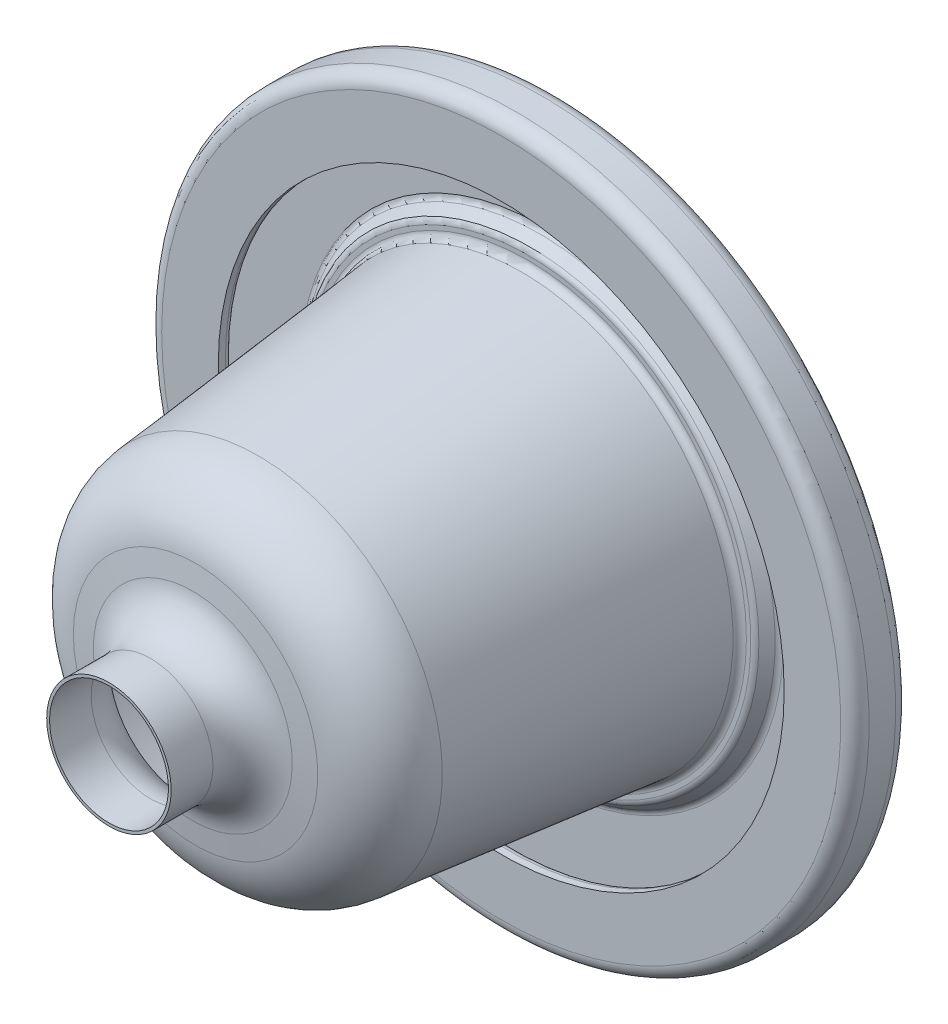
SolidWorks part; units mm, degrees
ref_plane "Front Plane" through (0, 0, 0) normal (0, 0, 1) x (1, 0, 0)
ref_plane "Top Plane" through (0, 0, 0) normal (0, 1, 0) x (1, 0, 0)
ref_plane "Right Plane" through (0, 0, 0) normal (1, 0, 0) x (0, 0, -1)
sketch "Sketch1" plane through (0, 0, 0) normal (0, 1, 0) x (1, 0, 0)
  line L0 (0, 0) -> (0, -30) construction
  line L1 (0, 2.4057) -> (0, 2.6057)
  line L2 (0, 2.6057) -> (15.8, 2.6057)
  line L3 (16, 2.4057) -> (16, 1.8057)
  line L4 (16.2, 1.6057) -> (24, 1.6057)
  line L5 (25, 0.6057) -> (25, -1.2732)
  line L6 (24, -2.2732) -> (20, -2.2732)
  line L7 (20, -2.2732) -> (20, -1.7732)
  line L8 (20.5, -1.2732) -> (23.5, -1.2732)
  line L9 (24, -0.7732) -> (24, -0.3943)
  line L10 (23, 0.6057) -> (17.0528, 0.6057)
  line L11 (16.6652, 0.4216) -> (16.1501, -0.2103)
  line L12 (15.7625, -0.3943) -> (15.4502, -0.3943)
  line L13 (14.953, -0.8421) -> (13, -19.4403)
  line L14 (8.6389, -23.8806) -> (7.0331, -24.0784)
  line L15 (4.4, -27.0559) -> (4.4, -30)
  line L16 (4.2, -30) -> (4.4, -30)
  line L17 (0.2, 2.4057) -> (0, 2.4057)
  line L18 (0.2, 2.4057) -> (15.6, 2.4057)
  line L19 (15.8, 2.2057) -> (15.8, 1.6057)
  line L20 (16, 1.4057) -> (23.8, 1.4057)
  line L21 (24.8, 0.4057) -> (24.8, -1.0732)
  line L22 (23.8, -2.0732) -> (20.2, -2.0732)
  line L23 (20.2, -2.0732) -> (20.2, -1.9732)
  line L24 (20.7, -1.4732) -> (23.7, -1.4732)
  line L25 (24.2, -0.9732) -> (24.2, -0.1943)
  line L26 (23.2, 0.8057) -> (16.9578, 0.8057)
  line L27 (16.5702, 0.6216) -> (16.0551, -0.0103)
  line L28 (15.6675, -0.1943) -> (15.2701, -0.1943)
  line L29 (14.7729, -0.6421) -> (12.8011, -19.4194)
  line L30 (8.6144, -23.6821) -> (7.0086, -23.8799)
  line L31 (4.2, -27.0559) -> (4.2, -30)
  line L32 (0.2, 0) -> (0.2, -30) construction
  line L33 (0, 0) -> (0, 2.4057) construction
  line L34 (0.2, 0) -> (0.2, 2.4057) construction
  line L35 (0, 0) -> (0, 2.6057) construction
  line L36 (15.8, 1.4057) -> (24.8, 1.4057) construction
  line L37 (15.8, 2.4057) -> (15.8, 1.4057) construction
  line L38 (16, 1.6057) -> (25, 1.6057) construction
  line L39 (16, 2.6057) -> (16, 1.6057) construction
  line L40 (0, 2.6057) -> (16, 2.6057) construction
  line L41 (0.2, 2.4057) -> (15.8, 2.4057) construction
  line L42 (24.8, 1.4057) -> (24.8, -2.0732) construction
  line L43 (24.8, -2.0732) -> (20.2, -2.0732) construction
  line L44 (25, -2.2732) -> (20, -2.2732) construction
  line L45 (25, 1.6057) -> (25, -2.2732) construction
  line L46 (24, -1.2732) -> (24, 0.6057) construction
  line L47 (24, 0.6057) -> (16.8153, 0.6057) construction
  line L48 (24.2, -1.4732) -> (24.2, 0.8057) construction
  line L49 (24.2, 0.8057) -> (16.7203, 0.8057) construction
  line L50 (20, -2.2732) -> (20, -1.2732) construction
  line L51 (20, -1.2732) -> (24, -1.2732) construction
  line L52 (20.2, -2.0732) -> (20.2, -1.4732) construction
  line L53 (20.2, -1.4732) -> (24.2, -1.4732) construction
  line L54 (15.905, -0.1943) -> (14.8199, -0.1943) construction
  line L55 (14.8199, -0.1943) -> (12.8011, -19.4194) construction
  line L56 (16, -0.3943) -> (15, -0.3943) construction
  line L57 (15, -0.3943) -> (13, -19.4403) construction
  line L58 (16.7203, 0.8057) -> (15.905, -0.1943) construction
  line L59 (16.8153, 0.6057) -> (16, -0.3943) construction
  arc A0 (13, -19.4403) -> (8.6389, -23.8806) centre (8.0273, -18.9181) cw
  arc A1 (4.4, -27.0559) -> (7.0331, -24.0784) centre (7.4, -27.0559) cw
  arc A2 (12.8011, -19.4194) -> (8.6144, -23.6821) centre (8.0273, -18.9181) cw
  arc A3 (4.2, -27.0559) -> (7.0086, -23.8799) centre (7.4, -27.0559) cw
  arc A4 (16, 1.4057) -> (15.8, 1.6057) centre (16, 1.6057) cw
  arc A5 (16.2, 1.6057) -> (16, 1.8057) centre (16.2, 1.8057) cw
  arc A6 (16, 2.4057) -> (15.8, 2.6057) centre (15.8, 2.4057) ccw
  arc A7 (15.8, 2.2057) -> (15.6, 2.4057) centre (15.6, 2.2057) ccw
  arc A8 (24.8, -1.0732) -> (23.8, -2.0732) centre (23.8, -1.0732) cw
  arc A9 (24, -2.2732) -> (25, -1.2732) centre (24, -1.2732) ccw
  arc A10 (24, -0.3943) -> (23, 0.6057) centre (23, -0.3943) ccw
  arc A11 (24.2, -0.1943) -> (23.2, 0.8057) centre (23.2, -0.1943) ccw
  arc A12 (24.8, 0.4057) -> (23.8, 1.4057) centre (23.8, 0.4057) ccw
  arc A13 (25, 0.6057) -> (24, 1.6057) centre (24, 0.6057) ccw
  arc A14 (20, -1.7732) -> (20.5, -1.2732) centre (20.5, -1.7732) cw
  arc A15 (20.2, -1.9732) -> (20.7, -1.4732) centre (20.7, -1.9732) cw
  arc A16 (24, -0.7732) -> (23.5, -1.2732) centre (23.5, -0.7732) cw
  arc A17 (23.7, -1.4732) -> (24.2, -0.9732) centre (23.7, -0.9732) ccw
  arc A18 (15.2701, -0.1943) -> (14.7729, -0.6421) centre (15.2701, -0.6943) ccw
  arc A19 (15.4502, -0.3943) -> (14.953, -0.8421) centre (15.4502, -0.8943) ccw
  arc A20 (16.0551, -0.0103) -> (15.6675, -0.1943) centre (15.6675, 0.3057) cw
  arc A21 (16.1501, -0.2103) -> (15.7625, -0.3943) centre (15.7625, 0.1057) cw
  arc A22 (16.9578, 0.8057) -> (16.5702, 0.6216) centre (16.9578, 0.3057) ccw
  arc A23 (17.0528, 0.6057) -> (16.6652, 0.4216) centre (17.0528, 0.1057) ccw
  point P21 (12.5848, -23.3943)
  point P24 (4.4, -24.4029)
  point P64 (25, -2.2732)
  point P95 (15, -0.3943)
  dimension "D12" = 5
  dimension "D13" = 3
  dimension "D18" = 0.2
  dimension "D2" = 1
  dimension "D19" = 0.5
  dimension "D20" = 0.5
  dimension "D1" = 30
  dimension "D3" = 25
  dimension "D4" = 1
  dimension "D5" = 1
  dimension "D6" = 2
  dimension "D7" = 1
  dimension "D8" = 1
  dimension "D10" = 15
  dimension "D11" = 23
  dimension "D14" = 4.4
  dimension "D15" = 13
  dimension "D16" = 5
  dimension "D17" = 0.2
revolve "Revolve1" add sketch "Sketch1" angle 360 about L0
